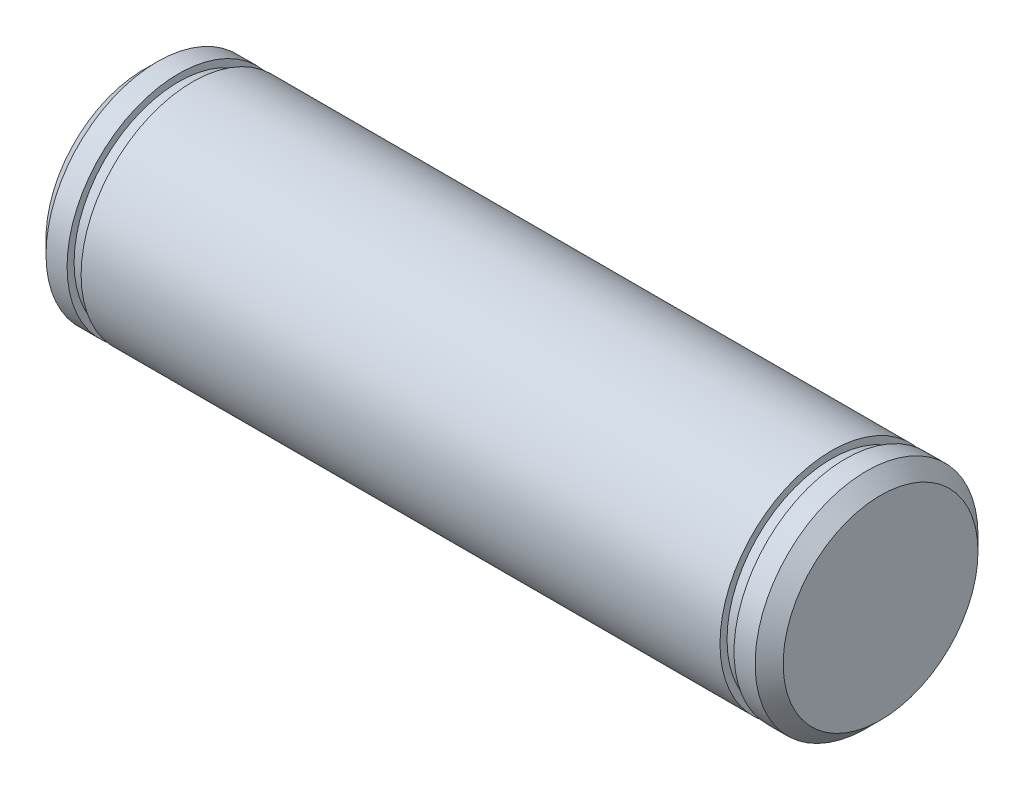
SolidWorks part; units mm, degrees
ref_plane "Front Plane" through (0, 0, 0) normal (0, 0, 1) x (1, 0, 0)
ref_plane "Top Plane" through (0, 0, 0) normal (0, 1, 0) x (1, 0, 0)
ref_plane "Right Plane" through (0, 0, 0) normal (1, 0, 0) x (0, 0, -1)
sketch "Sketch2" plane through (0, 0, 0) normal (1, 0, 0) x (0, 0, -1)
  circle A0 centre (0, 0) radius 15.875
extrude "Boss-Extrude1" add sketch "Sketch2" along normal mid plane 105
chamfer "Chamfer2" distance 2 angle 45 2 edges at (-52.5, 0, -15.875) (52.5, 0, -15.875)
ref_plane "Plane1" through (-47.5, 0, 0) normal (-1, 0, 0) x (0, 0, 1)
sketch "Sketch4" plane through (-47.5, 0, 0) normal (-1, 0, 0) x (0, 0, 1)
  circle A0 centre (0, 0) radius 15.9328
  circle A1 centre (0, 0) radius 14.875
extrude "Cut-Extrude5" cut sketch "Sketch4" against normal blind 2 flip side to cut contours A1
mirror "Mirror1" about plane through (0, 0, 0) normal (1, 0, 0) of "Cut-Extrude5"
